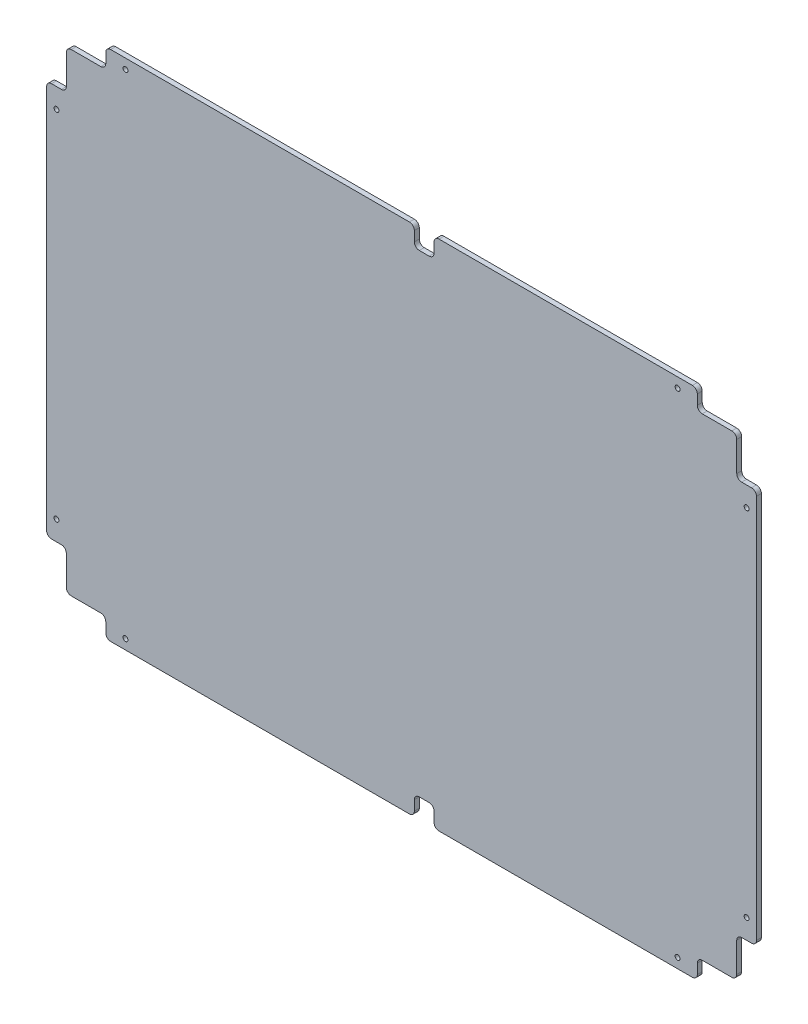
SolidWorks part; units mm, degrees
material "环氧树脂,未充填"
ref_plane "前视基准面" through (0, 0, 0) normal (0, 0, 1) x (1, 0, 0)
ref_plane "上视基准面" through (0, 0, 0) normal (0, 1, 0) x (1, 0, 0)
ref_plane "右视基准面" through (0, 0, 0) normal (1, 0, 0) x (0, 0, -1)
sketch "草图1" plane through (0, 0, 0) normal (0, 0, 1) x (1, 0, 0)
  line L1 (-360, 260) -> (360, 260)
  line L2 (-360, 260) -> (-360, -260)
  line L3 (-360, -260) -> (360, -260)
  line L4 (360, 260) -> (360, -260)
  line L5 (-360, 260) -> (360, -260) construction
  line L6 (-360, -260) -> (360, 260) construction
  point P0 (0, 0)
  dimension "D1" = 720
  dimension "D2" = 520
extrude "凸台-拉伸1" add sketch "草图1" along normal blind 5
sketch "草图2" plane through (0, 0, 5) normal (0, 0, 1) x (1, 0, 0)
  line L4 (340, -240) -> (340, -200)
  line L5 (340, 240) -> (300, 240)
  line L6 (-340, 240) -> (-340, 200)
  line L7 (-340, -240) -> (-300, -240)
  line L8 (360, -260) -> (360, 260)
  line L9 (360, 260) -> (-360, 260)
  line L10 (-360, 260) -> (-360, -260)
  line L11 (-360, -260) -> (360, -260)
  line L12 (360, -260) -> (360, -200)
  line L13 (360, 260) -> (300, 260)
  line L14 (-360, 260) -> (-360, 200)
  line L15 (-360, -260) -> (-300, -260)
  line L16 (360, 200) -> (340, 200)
  line L17 (300, 260) -> (300, 240)
  line L18 (360, -200) -> (340, -200)
  line L19 (300, -240) -> (300, -260)
  line L20 (-300, -240) -> (-300, -260)
  line L21 (-340, -200) -> (-360, -200)
  line L22 (-300, 240) -> (-300, 260)
  line L23 (-340, 200) -> (-360, 200)
  line L24 (-300, 240) -> (-340, 240)
  line L25 (340, 240) -> (-340, 240) construction
  line L26 (-300, 260) -> (-360, 260)
  line L27 (360, 260) -> (-360, 260) construction
  line L28 (300, -240) -> (340, -240)
  line L29 (-340, -240) -> (340, -240) construction
  line L30 (300, -260) -> (360, -260)
  line L31 (-360, -260) -> (360, -260) construction
  line L32 (340, 200) -> (340, 240)
  line L33 (340, -240) -> (340, 240) construction
  line L34 (360, 200) -> (360, 260)
  line L35 (360, -260) -> (360, 260) construction
  line L36 (-340, -200) -> (-340, -240)
  line L37 (-340, 240) -> (-340, -240) construction
  line L38 (-360, -200) -> (-360, -260)
  line L39 (-360, 260) -> (-360, -260) construction
  dimension "D3" = 60
  dimension "D4" = 60
  dimension "D5" = 60
  dimension "D6" = 60
  dimension "D1" = 0
  dimension "D2" = 20
extrude "切除-拉伸1" cut sketch "草图2" against normal through all
sketch "草图3" plane through (0, 0, 5) normal (0, 0, 1) x (1, 0, 0)
  line L0 (360, -200) -> (360, 200) construction
  line L1 (340, 200) -> (360, 200) construction
  line L2 (300, 260) -> (300, 240) construction
  line L3 (300, 260) -> (-300, 260) construction
  line L4 (360, -200) -> (340, -200) construction
  line L5 (300, -240) -> (300, -260) construction
  line L6 (-300, -260) -> (300, -260) construction
  line L7 (-300, -260) -> (-300, -240) construction
  line L8 (-360, 200) -> (-360, -200) construction
  line L9 (-340, -200) -> (-360, -200) construction
  line L10 (-300, 240) -> (-300, 260) construction
  line L11 (-360, 200) -> (-340, 200) construction
  line L12 (-360, 200) -> (-360, -200) construction
  circle A0 centre (350, 180) radius 2.5
  circle A1 centre (280, 250) radius 2.5
  circle A2 centre (-280, 250) radius 2.5
  circle A3 centre (-350, 180) radius 2.5
  circle A4 centre (-350, -180) radius 2.5
  circle A5 centre (-280, -250) radius 2.5
  circle A6 centre (350, -180) radius 2.5
  circle A7 centre (280, -250) radius 2.5
  point P38 (-300, 250)
  dimension "D1" = 5
  dimension "D2" = 10
  dimension "D3" = 20
  dimension "D4" = 5
  dimension "D5" = 20
  dimension "D6" = 10
  dimension "D7" = 5
  dimension "D8" = 10
  dimension "D10" = 20
  dimension "D12" = 5
  dimension "D13" = 5
  dimension "D14" = 20
  dimension "D15" = 10
  dimension "D16" = 5
  dimension "D17" = 10
  dimension "D18" = 20
  dimension "D19" = 5
  dimension "D20" = 5
  dimension "D21" = 20
  dimension "D22" = 10
  dimension "D23" = 20
  dimension "D24" = 10
  dimension "D9" = 20
  dimension "D11" = 10
extrude "切除-拉伸2" cut sketch "草图3" against normal through all
sketch "草图4" plane through (0, 0, 5) normal (0, 0, 1) x (1, 0, 0)
  line L2 (13, 260) -> (13, 240)
  line L3 (300, 260) -> (-300, 260) construction
  line L4 (13, 240) -> (33, 240)
  line L5 (33, 240) -> (33, 260)
  line L6 (33, 260) -> (13, 260)
  line L7 (-360, 200) -> (-360, -200) construction
  dimension "D1" = 373
  dimension "D2" = 20
  dimension "D3" = 20
extrude "切除-拉伸3" cut sketch "草图4" against normal blind 10
mirror "镜向2" about plane through (0, 0, 0) normal (0, 1, 0) of "切除-拉伸3"
fillet "圆角1" radius 5 28 edges at (300, -260, 2.5) (300, -240, 2.5) (360, -200, 2.5) (340, -240, 2.5) (340, -200, 2.5) (-300, -260, 2.5) (-300, -240, 2.5) (-340, -240, 2.5) (-340, -200, 2.5) (-360, -200, 2.5) (-360, 200, 2.5) (-340, 200, 2.5) (-340, 240, 2.5) (-300, 240, 2.5) (-300, 260, 2.5) (300, 260, 2.5) (300, 240, 2.5) (340, 240, 2.5) (340, 200, 2.5) (360, 200, 2.5) (13, -260, 2.5) (13, -240, 2.5) (33, -260, 2.5) (33, -240, 2.5) (33, 260, 2.5) (33, 240, 2.5) (13, 240, 2.5) (13, 260, 2.5)
